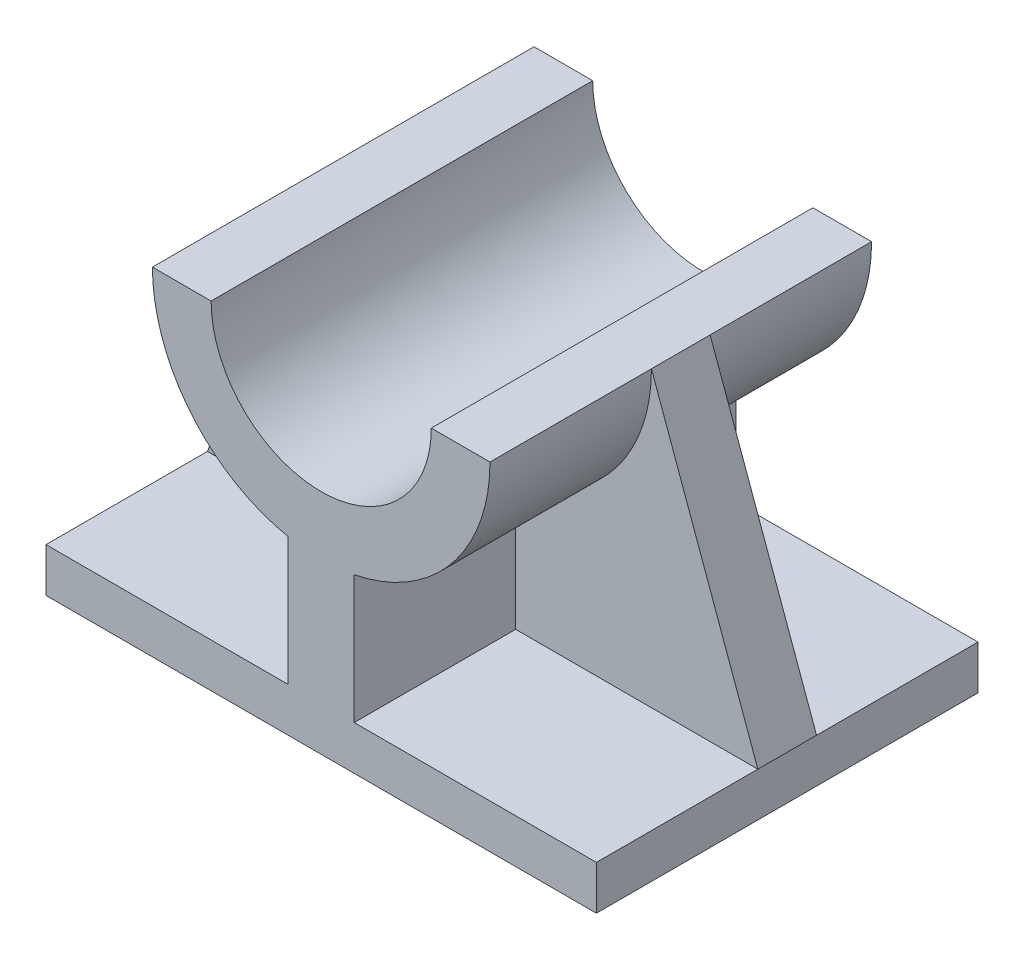
SolidWorks part; units mm, degrees
ref_plane "Front Plane" through (0, 0, 0) normal (0, 0, 1) x (1, 0, 0)
ref_plane "Top Plane" through (0, 0, 0) normal (0, 1, 0) x (1, 0, 0)
ref_plane "Right Plane" through (0, 0, 0) normal (1, 0, 0) x (0, 0, -1)
sketch "Sketch1" plane through (0, 0, 0) normal (0, 0, 1) x (1, 0, 0)
  line L0 (-23, 43) -> (-15, 43)
  line L1 (-37.5, 3) -> (-4.5, 3)
  line L2 (-37.5, 3) -> (-37.5, -3)
  line L3 (-37.5, -3) -> (37.5, -3)
  line L4 (37.5, 3) -> (37.5, -3)
  line L5 (-37.5, 3) -> (37.5, -3) construction
  line L6 (-37.5, -3) -> (37.5, 3) construction
  line L7 (15, 43) -> (23, 43)
  line L8 (-4.5, 3) -> (-4.5, 20.4445)
  line L9 (0, -5.8425) -> (0, 30.5395) construction
  line L10 (4.5, 3) -> (4.5, 20.4445)
  line L11 (4.5, 3) -> (37.5, 3)
  arc A0 (-23, 43) -> (-4.5, 20.4445) centre (0, 43) ccw
  arc A1 (-15, 43) -> (15, 43) centre (0, 43) ccw
  arc A2 (4.5, 20.4445) -> (23, 43) centre (0, 43) ccw
  point P0 (0, 0)
  dimension "D3" = 46
  dimension "D4" = 30
  dimension "D1" = 75
  dimension "D2" = 6
  dimension "D5" = 40
  dimension "D6" = 4.5
extrude "Boss-Extrude1" add sketch "Sketch1" along normal mid plane 52 contours A0 L8 L1 L2 L3 L4 L11 L10 A2 L7 A1 L0
sketch "Sketch2" plane through (0, 0, 0) normal (0, 0, 1) x (1, 0, 0)
  line L0 (23, 43) -> (37.5, 3)
rib "Rib1" sketch "Sketch2" sketch "Sketch2" thickness 8 extrusion direction parallel to sketch draft on no parameters "D1"=8
mirror "Mirror1" about plane through (0, 0, 0) normal (1, 0, 0) of "Rib1"
